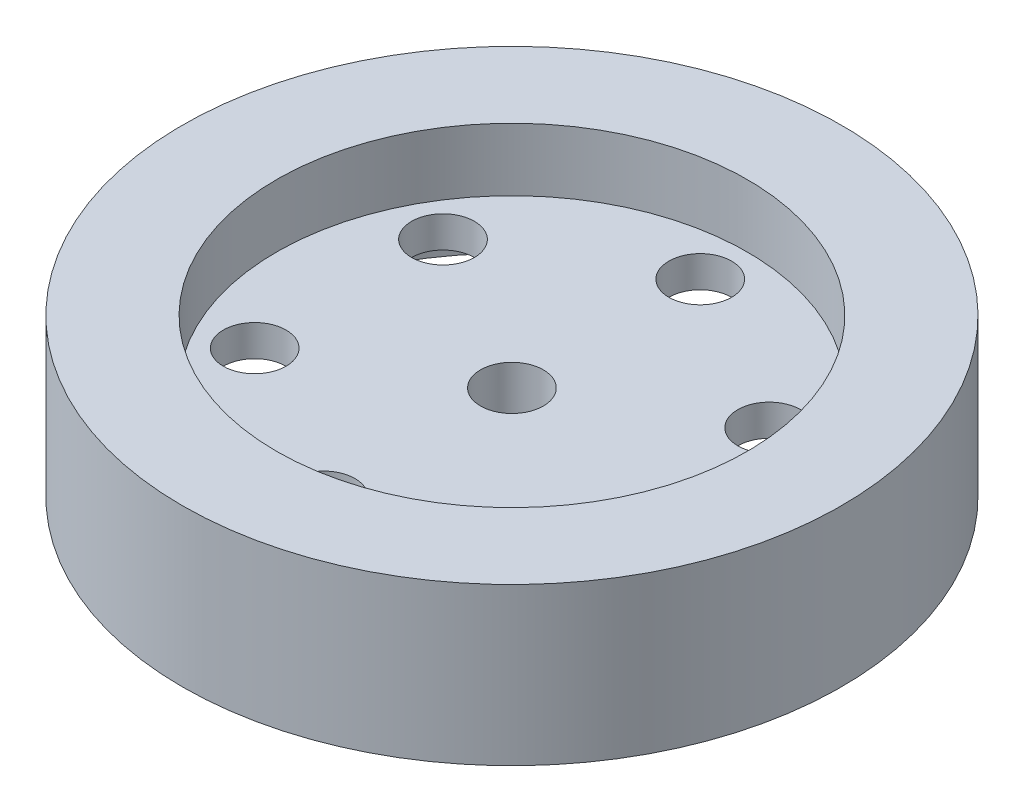
SolidWorks part; units mm, degrees
material "Zinc AC41A Alloy, As Cast"
ref_plane "Front Plane" through (0, 0, 0) normal (0, 0, 1) x (1, 0, 0)
ref_plane "Top Plane" through (0, 0, 0) normal (0, 1, 0) x (1, 0, 0)
ref_plane "Right Plane" through (0, 0, 0) normal (1, 0, 0) x (0, 0, -1)
sketch "Sketch1" plane through (0, 0, 0) normal (0, 1, 0) x (1, 0, 0)
  circle A0 centre (0, 0) radius 21
  dimension "D1" = 42
extrude "Boss-Extrude1" add sketch "Sketch1" along normal blind 10
sketch "Sketch2" plane through (0, 10, 0) normal (0, 1, 0) x (1, 0, 0)
  circle A0 centre (0, 0) radius 15
  dimension "D1" = 30
extrude "Cut-Extrude1" cut sketch "Sketch2" against normal blind 4
sketch "Sketch3" plane through (0, 0, 0) normal (0, -1, 0) x (1, 0, 0)
  circle A0 centre (0, 0) radius 19
  circle A1 centre (0, 0) radius 5
  dimension "D1" = 38
  dimension "D2" = 10
extrude "Cut-Extrude2" cut sketch "Sketch3" against normal blind 4
sketch "Sketch4" plane through (0, 0, 0) normal (0, -1, 0) x (1, 0, 0)
  circle A0 centre (0, 0) radius 2
  dimension "D1" = 4
extrude "Cut-Extrude3" cut sketch "Sketch4" against normal through all
sketch "Sketch5" plane through (0, 4, 0) normal (0, -1, 0) x (1, 0, 0)
  circle A0 centre (0, 0) radius 12 construction
  circle A1 centre (0, 12) radius 2
  circle A2 centre (10.3923, 6) radius 2
  circle A3 centre (10.3923, -6) radius 2
  circle A4 centre (0, -12) radius 2
  circle A5 centre (-10.3923, -6) radius 2
  circle A6 centre (-10.3923, 6) radius 2
  point P18 (0, 0)
  dimension "D1" = 24
  dimension "D2" = 4
  dimension "D3" = 6
extrude "Cut-Extrude4" cut sketch "Sketch5" against normal through all
